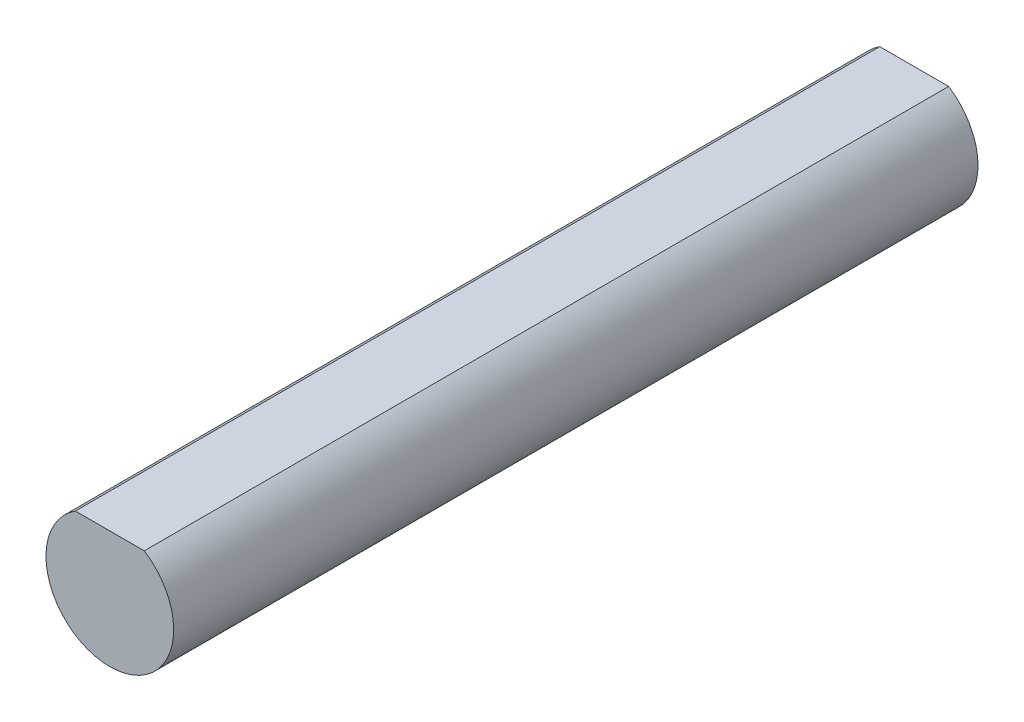
SolidWorks part; units mm, degrees
ref_plane "Front Plane" through (0, 0, 0) normal (0, 0, 1) x (1, 0, 0)
ref_plane "Top Plane" through (0, 0, 0) normal (0, 1, 0) x (1, 0, 0)
ref_plane "Right Plane" through (0, 0, 0) normal (1, 0, 0) x (0, 0, -1)
sketch "Sketch1" plane through (0, 0, 0) normal (0, 0, 1) x (1, 0, 0)
  line L0 (-1.7145, 2.6723) -> (1.7145, 2.6723)
  arc A0 (-1.7145, 2.6723) -> (1.7145, 2.6723) centre (0, 0) ccw
  dimension "D1" = 6.35
  dimension "D2" = 3.429
extrude "Boss-Extrude1" add sketch "Sketch1" along normal blind 40
